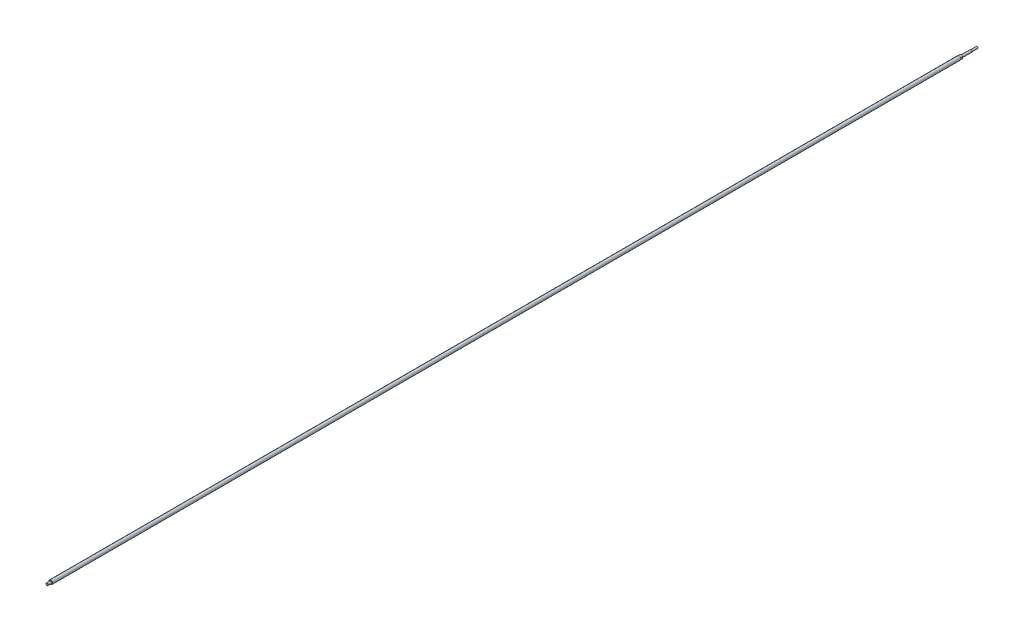
SolidWorks part; units mm, degrees
ref_plane "Front Plane" through (0, 0, 0) normal (0, 0, 1) x (1, 0, 0)
ref_plane "Top Plane" through (0, 0, 0) normal (0, 1, 0) x (1, 0, 0)
ref_plane "Right Plane" through (0, 0, 0) normal (1, 0, 0) x (0, 0, -1)
sketch "Sketch1" plane through (0, 0, 0) normal (0, 0, 1) x (1, 0, 0)
  circle A0 centre (0, 0) radius 5
  dimension "D1" = 10
extrude "Boss-Extrude1" add sketch "Sketch1" along normal blind 2500
sketch "Sketch2" plane through (0, 0, 0) normal (0, 0, -1) x (-1, 0, 0)
  circle A0 centre (0, 0) radius 4.75
  circle M2 centre (0, 0) radius 5
  dimension "D1" = 9.5
extrude "Cut-Extrude1" cut sketch "Sketch2" against normal blind 49.5 contours A0 M2
sketch "Sketch3" plane through (0, 0, 0) normal (0, 0, -1) x (-1, 0, 0)
  circle A0 centre (0, 0) radius 3
  circle M2 centre (0, 0) radius 4.75
  dimension "D1" = 6
extrude "Cut-Extrude2" cut sketch "Sketch3" against normal blind 43 contours A0 M2
sketch "Sketch5" plane through (0, 0, 43) normal (0, 0, -1) x (-1, 0, 0)
  line L0 (-4, 2.5617) -> (-4, -2.5617)
  line L1 (4, 2.5617) -> (4, -2.5617)
  arc A0 (4, -2.5617) -> (4, 2.5617) centre (0, 0) ccw
  circle A1 centre (0, 0) radius 4.75
  arc A2 (-4, 2.5617) -> (-4, -2.5617) centre (0, 0) ccw
  dimension "D2" = 8
  dimension "D1" = 0
extrude "Cut-Extrude3" cut sketch "Sketch5" against normal up to surface (6.5 mm away) up to face at (-4.75, 0, 49.5)
sketch "Sketch6" plane through (0, 0, 0) normal (0, 0, -1) x (-1, 0, 0)
  circle A0 centre (0, 0) radius 2.5
  circle M2 centre (0, 0) radius 3
  dimension "D1" = 5
extrude "Cut-Extrude4" cut sketch "Sketch6" against normal blind 16 contours A0 M2
sketch "Sketch7" plane through (0, 0, 2500) normal (0, 0, 1) x (1, 0, 0)
  circle A0 centre (0, 0) radius 3
  circle M2 centre (0, 0) radius 5
  dimension "D1" = 6
extrude "Cut-Extrude5" cut sketch "Sketch7" against normal blind 10 contours A0 M2
